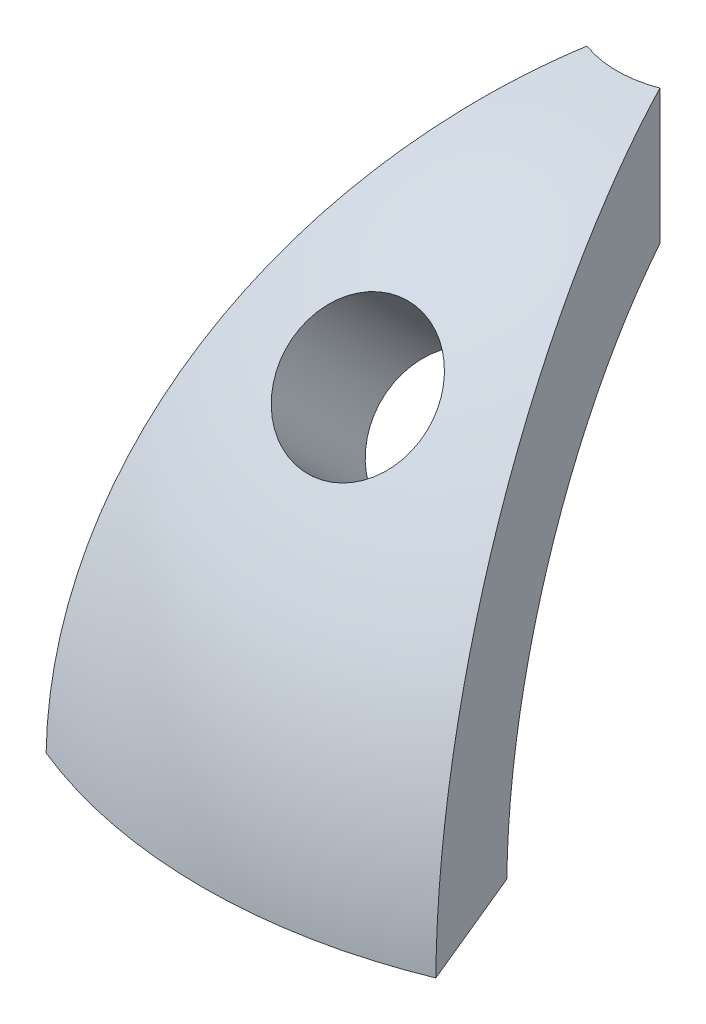
SolidWorks part; units mm, degrees
ref_plane "Front Plane" through (0, 0, 0) normal (0, 0, 1) x (1, 0, 0)
ref_plane "Top Plane" through (0, 0, 0) normal (0, 1, 0) x (1, 0, 0)
ref_plane "Right Plane" through (0, 0, 0) normal (1, 0, 0) x (0, 0, -1)
sketch "Sketch1" plane through (0, 0, 0) normal (1, 0, 0) x (0, 0, -1)
  line L1 (19.05, 0) -> (-19.05, 0) construction
  line L2 (-3.81, 13.4404) -> (-3.81, 9.4186) construction
  line L3 (-14.2178, 0.25) -> (-19.0484, 0.25)
  line L4 (-3.81, 18.6651) -> (-3.81, 13.7001)
  line L5 (0, 0) -> (0, 50000) construction
  arc A0 (-3.81, 13.4404) -> (-13.97, 0) centre (0, 0) ccw construction
  arc A1 (-3.81, 13.4404) -> (-13.97, 0) centre (0, 0) ccw construction
  arc A2 (-3.81, 13.7001) -> (-14.2178, 0.25) centre (0, 0) ccw
  arc A3 (-2.4953, 13.7453) -> (-13.97, 0) centre (0, 0) ccw construction
  arc A4 (-3.81, 18.6651) -> (-19.0484, 0.25) centre (0, 0) ccw
  arc A5 (-2.54, 13.9913) -> (-14.22, 0) centre (0, 0) ccw construction
  arc A6 (-19.05, 0) -> (19.05, 0) centre (0, 0) ccw construction
  dimension "D2" = 0.25
  dimension "D1" = 0.25
revolve "Revolve1" add sketch "Sketch1" angle 45 mid plane about L5
sketch "Sketch2" plane through (0, 0, 0) normal (0, 1, 0) x (1, 0, 0)
  line L0 (7.2895, -17.5984) -> (1.458, -3.52) construction
  line L1 (7.2895, -17.5984) -> (1.458, -3.52)
  line L2 (7.1738, -17.6458) -> (1.3418, -3.5659)
  line L3 (7.174, -17.6462) -> (1.3425, -3.5678) construction
  line L4 (0, 0) -> (0, -50000) construction
  line L5 (-7.1738, -17.6458) -> (-1.3418, -3.5659)
  line L6 (-7.2895, -17.5984) -> (-1.458, -3.52)
  arc A0 (-7.2895, -17.5984) -> (7.2895, -17.5984) centre (0, 0) ccw construction
  arc A1 (-1.458, -3.52) -> (1.458, -3.52) centre (0, 0) ccw construction
  arc A2 (7.1738, -17.6458) -> (7.2895, -17.5984) centre (0, 0) ccw
  arc A3 (1.3418, -3.5659) -> (1.458, -3.52) centre (0, 0) ccw
  arc A4 (-1.3418, -3.5659) -> (-1.458, -3.52) centre (0, 0) cw
  arc A5 (-7.1738, -17.6458) -> (-7.2895, -17.5984) centre (0, 0) cw
  dimension "D1" = 0.125
extrude "Cut-Extrude1" cut sketch "Sketch2" against normal through all both and the other way through all
ref_plane "Plane1" through (0, 0, 0) normal (0, 0.7071, 0.7071) x (-1, 0, 0)
ref_plane "Plane2" through (0, 0, 0) normal (0, 0.3827, 0.9239) x (-1, 0, 0)
sketch "Sketch8" plane through (0, 0, 0) normal (0, 0.3827, 0.9239) x (-1, 0, 0)
  line L0 (-18.6381, 3.9399) -> (18.6381, 3.9399) construction
  arc A0 (8.7263, 16.9338) -> (-8.7265, 16.9337) centre (0, 0) ccw construction
  ellipse E0 centre (0, -0.231) end of major axis (14.2178, -0.231) minor radius 5.4409 (5.3252, 4.8139) -> (-5.3252, 4.8139) ccw construction
  ellipse E1 centre (0, -0.231) end of major axis (14.2178, -0.231) minor radius 5.4409 (5.3252, 4.8139) -> (-5.3252, 4.8139) ccw construction
  text T0 "<r180>    1</r>" font "Century Gothic" height 4.445
  point P3 (0, 3.9399)
  dimension "D1" = 2.54
extrude "Cut-Extrude4" cut sketch "Sketch8" along normal blind 0.381 from surface starting at face at (0, 7.8389, 9.7254)
ref_plane "Plane3" through (0, 18.8585, 18.8585) normal (0, 0.7071, 0.7071) x (1, 0, 0)
sketch "Sketch9" plane through (0, 18.8585, 18.8585) normal (0, 0.7071, 0.7071) x (1, 0, 0)
  circle A0 centre (0, 0) radius 2.6035
  dimension "D1" = 5.207
extrude "Cut-Extrude5" cut sketch "Sketch9" against normal through all both and the other way through all
